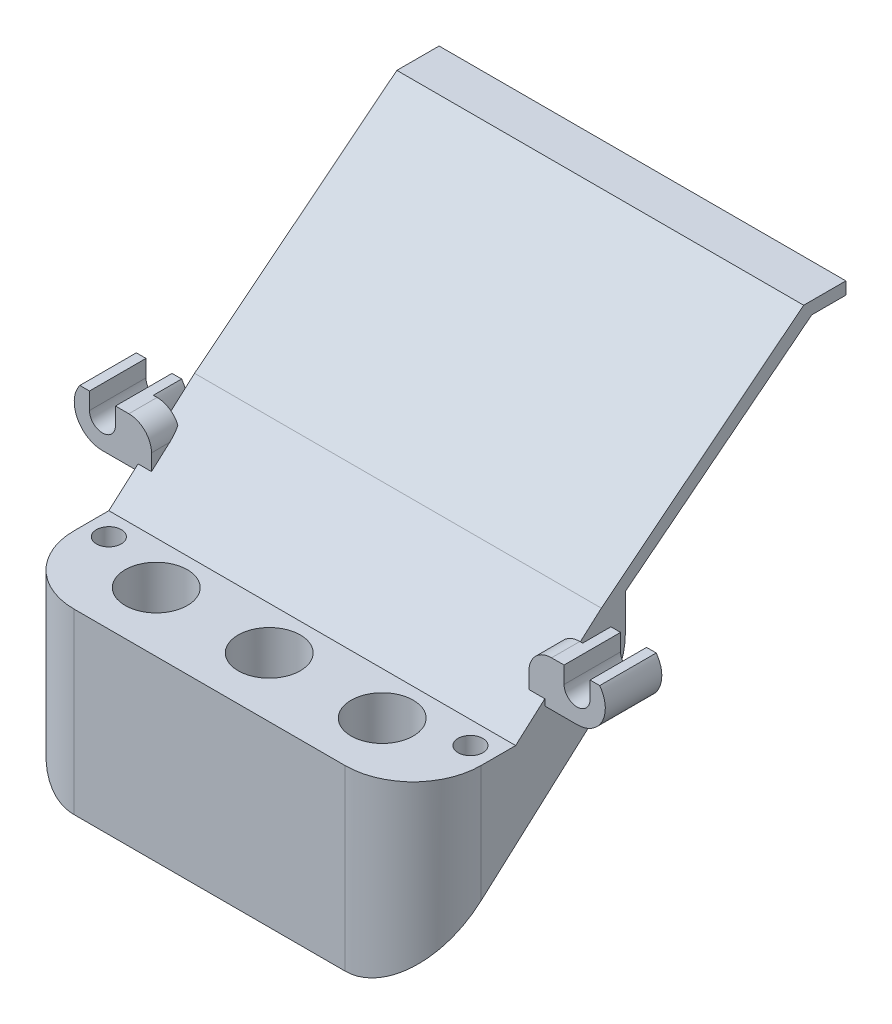
SolidWorks part; units mm, degrees
ref_plane "Plan de face" through (0, 0, 0) normal (0, 0, 1) x (1, 0, 0)
ref_plane "Plan de dessus" through (0, 0, 0) normal (0, 1, 0) x (1, 0, 0)
ref_plane "Plan de droite" through (0, 0, 0) normal (1, 0, 0) x (0, 0, -1)
sketch "Esquisse1" plane through (0, 0, 0) normal (0, 0, 1) x (1, 0, 0)
  circle A0 centre (20.8519, -74.7328) radius 1.15 construction
  circle A1 centre (20.8519, -74.7328) radius 2.5 construction
  circle A2 centre (-21.1481, -74.7328) radius 1.15 construction
  circle A3 centre (-21.1481, -74.7328) radius 2.5 construction
  circle A4 centre (20.8519, -74.7328) radius 1.15
  circle A5 centre (20.8519, -74.7328) radius 2.5
  circle A6 centre (-21.1481, -74.7328) radius 1.15
  circle A7 centre (-21.1481, -74.7328) radius 2.5
extrude "Extrusion1" add sketch "Esquisse1" along normal blind 5
ref_plane "Plan1" through (-0.172, -44.3624, -39.7148) normal (0.0029, 0.7451, 0.667) x (-1, 0.0022, 0.0019)
ref_plane "Plan3" through (0, 0, 2.5) normal (0, 0, -1) x (-1, 0, 0)
sketch "Esquisse2" plane through (0, 0, 0) normal (1, 0, 0) x (0, 0, -1)
  line L0 (-16.6644, -94.7252) -> (-16.6644, -78.9708)
  line L1 (-16.6644, -78.9708) -> (-7.5847, -78.9708)
  line L4 (0, -72.2328) -> (-7.5847, -78.9708)
  line L6 (13.7264, -67.586) -> (13.6952, -67.5462)
  line L7 (13.6952, -67.5462) -> (-23.5219, -100.8643)
  line L8 (-23.4201, -100.9942) -> (-23.4187, -100.9961)
  line L9 (-23.4187, -100.9961) -> (-14.2215, -92.7624)
  line L10 (-9.7404, -88.7476) -> (13.797, -67.6761)
  line L11 (13.797, -67.6761) -> (13.7653, -67.6356)
  line L13 (13.6952, -67.5462) -> (-16.6644, -94.7252)
  line L15 (0, -77.2328) -> (0, -72.2328) construction
  line L16 (0, -72.2328) -> (17.9041, -57.9669)
  line L17 (15.9956, -57.9652) -> (21.6434, -57.9702) construction
  line L18 (17.9041, -57.9669) -> (21.6434, -57.9702)
  line L19 (21.6434, -57.9702) -> (21.6415, -60.1702)
  line L20 (21.6415, -60.1702) -> (13.6952, -67.5462)
  spline S3 degree 3 poles (13.7653, -67.6356) (5.4607, -75.1113) (-5.0997, -84.5418) (-5.1272, -84.5067) (-5.1548, -84.4715) (5.3839, -75.0134) (13.7264, -67.586) knots 0 0 0 0 0.5 0.5 0.5 1 1 1 1 weights 1 0.596334 0.596334 1 0.596334 0.596334 1
  spline S4 degree 3 poles (-23.5219, -100.8643) (-19.5236, -97.3576) (-19.4888, -97.402) (-23.4201, -100.9942) knots 0 0 0 0 1 1 1 1 weights 1 0.974679 0.974679 1
  spline S5 degree 3 poles (-14.2215, -92.7624) (-12.7257, -91.4223) (-11.231, -90.0832) (-9.7404, -88.7476) knots 0 0 0 0 1 1 1 1
  dimension "D1" = 0
extrude "Extrusion2" add sketch "Esquisse2" along normal mid plane 36
sketch "Esquisse3" plane through (0, 0, 2.5) normal (0, 0, 1) x (1, 0, 0)
  line L0 (-23.1526, -73.2388) -> (-22.2981, -73.2388)
  line L1 (18.8474, -73.2388) -> (19.7019, -73.2388)
  line L2 (-22.2981, -74.7328) -> (-22.2981, -73.2388)
  line L3 (-19.9981, -73.2388) -> (-19.1436, -73.2388)
  line L4 (-19.9981, -74.7328) -> (-19.9981, -73.2388)
  line L5 (-21.1481, -77.2328) -> (-16.8122, -77.2328)
  line L6 (19.7019, -74.7328) -> (19.7019, -73.2388)
  line L8 (22.0019, -74.7328) -> (22.0019, -73.2388)
  line L9 (22.0019, -73.2388) -> (22.8564, -73.2388)
  line L10 (-16.8122, -77.2328) -> (-16.8122, -73.2388)
  line L11 (-16.8122, -73.2388) -> (-19.1436, -73.2388)
  line L12 (18.8474, -73.2388) -> (16.5967, -73.2388)
  line L13 (16.5967, -73.2388) -> (16.5967, -77.2328)
  line L14 (16.5967, -77.2328) -> (20.8519, -77.2328)
  circle A2 centre (-21.1481, -74.7328) radius 2.5 construction
  circle A3 centre (-21.1481, -74.7328) radius 1.15 construction
  arc A4 (-23.1526, -73.2388) -> (-21.1481, -77.2328) centre (-21.1481, -74.7328) ccw
  arc A5 (-22.2981, -74.7328) -> (-19.9981, -74.7328) centre (-21.1481, -74.7328) ccw
  circle A6 centre (20.8519, -74.7328) radius 2.5 construction
  circle A7 centre (20.8519, -74.7328) radius 1.15 construction
  arc A8 (20.8519, -77.2328) -> (22.8564, -73.2388) centre (20.8519, -74.7328) ccw
  arc A9 (19.7019, -74.7328) -> (22.0019, -74.7328) centre (20.8519, -74.7328) ccw
extrude "Extrusion3" add sketch "Esquisse3" along normal blind 2.5
sketch "Esquisse4" plane through (0, -78.9708, 0) normal (0, 1, 0) x (-1, 0, 0)
  circle A0 centre (-9.9928, 11.3854) radius 2.75
  circle A1 centre (-9.9928, 11.3854) radius 2.75
  circle A2 centre (0.0072, 11.3828) radius 2.75
  circle A3 centre (0.0072, 11.3828) radius 2.75
  circle A4 centre (10.0072, 11.3803) radius 2.75
  circle A5 centre (10.0072, 11.3803) radius 2.75
  dimension "D1" = 0
  dimension "D2" = 0
  dimension "D3" = 0
extrude "Enlèv. mat.-Extru.1" cut sketch "Esquisse4" against normal through all and the other way through all
fillet "Congé3" radius 2 2 edges at (-16.8122, -73.2388, 3.75) (16.5967, -73.2388, 3.75)
sketch "Esquisse5" plane through (0, 0, 5) normal (0, 0, 1) x (1, 0, 0)
  circle A0 centre (-21.1481, -74.7328) radius 2.5 construction
  circle A1 centre (-21.1481, -74.7328) radius 1.15 construction
  circle A2 centre (20.8519, -74.7328) radius 1.15 construction
  circle A3 centre (20.8519, -74.7328) radius 2.5 construction
  circle A4 centre (-21.1481, -74.7328) radius 2.5
  circle A5 centre (-21.1481, -74.7328) radius 1.15
  circle A6 centre (20.8519, -74.7328) radius 1.15
  circle A7 centre (20.8519, -74.7328) radius 2.5
extrude "Enlèv. mat.-Extru.2" [suppressed] cut sketch "Esquisse5" against normal blind 2.5
sketch "Esquisse6" plane through (0, 0, 5) normal (0, 0, 1) x (1, 0, 0)
  line L7 (19.7019, -73.2388) -> (18.8474, -73.2388)
  line L8 (18.8474, -73.2388) -> (16.5967, -73.2388)
  line L9 (16.5967, -73.2388) -> (16.5967, -77.2328)
  line L10 (16.5967, -77.2328) -> (20.8519, -77.2328)
  line L11 (22.8564, -73.2388) -> (22.0019, -73.2388)
  line L12 (22.0019, -73.2388) -> (22.0019, -74.7328)
  line L13 (19.7019, -74.7328) -> (19.7019, -73.2388)
  line L14 (19.7019, -73.2388) -> (18.8474, -73.2388)
  line L18 (22.8564, -73.2388) -> (22.0019, -73.2388)
  line L19 (22.0019, -73.2388) -> (22.0019, -74.7328)
  line L20 (19.7019, -74.7328) -> (19.7019, -73.2388)
  line L21 (-21.1481, -77.2328) -> (-16.8122, -77.2328)
  line L22 (-16.8122, -77.2328) -> (-16.8122, -73.2388)
  line L23 (-16.8122, -73.2388) -> (-19.1436, -73.2388)
  line L24 (-19.1436, -73.2388) -> (-19.9981, -73.2388)
  line L25 (-19.9981, -73.2388) -> (-19.9981, -74.7328)
  line L26 (-22.2981, -74.7328) -> (-22.2981, -73.2388)
  line L27 (-22.2981, -73.2388) -> (-23.1526, -73.2388)
  line L31 (-19.1436, -73.2388) -> (-19.9981, -73.2388)
  line L32 (-19.9981, -73.2388) -> (-19.9981, -74.7328)
  line L33 (-22.2981, -74.7328) -> (-22.2981, -73.2388)
  line L34 (-22.2981, -73.2388) -> (-23.1526, -73.2388)
  arc A0 (20.8519, -77.2328) -> (18.8474, -73.2388) centre (20.8519, -74.7328) ccw construction
  arc A1 (22.8564, -73.2388) -> (18.8474, -73.2388) centre (20.8519, -74.7328) ccw
  arc A2 (20.8519, -77.2328) -> (22.8564, -73.2388) centre (20.8519, -74.7328) ccw
  arc A3 (19.7019, -74.7328) -> (22.0019, -74.7328) centre (20.8519, -74.7328) ccw
  arc A4 (-19.1436, -73.2388) -> (-21.1481, -77.2328) centre (-21.1481, -74.7328) ccw construction
  arc A5 (19.7019, -74.7328) -> (22.0019, -74.7328) centre (20.8519, -74.7328) ccw
  arc A6 (-23.1526, -73.2388) -> (-21.1481, -77.2328) centre (-21.1481, -74.7328) ccw
  arc A7 (-22.2981, -74.7328) -> (-19.9981, -74.7328) centre (-21.1481, -74.7328) ccw
  arc A9 (-22.2981, -74.7328) -> (-19.9981, -74.7328) centre (-21.1481, -74.7328) ccw
  arc A10 (-19.1436, -73.2388) -> (-23.1526, -73.2388) centre (-21.1481, -74.7328) ccw
  dimension "D1" = 0
  dimension "D2" = 0
extrude "Enlèv. mat.-Extru.3" cut sketch "Esquisse6" against normal through all
sketch "Esquisse7" plane through (18, 0, 0) normal (1, 0, 0) x (0, 0, -1)
  line L0 (22.3876, -59.0664) -> (18.6199, -59.0664)
  line L2 (18.6199, -59.0664) -> (2.1273, -72.0094)
  line L3 (2.1273, -72.0094) -> (2.1273, -79.6896)
  line L4 (2.1273, -79.6896) -> (22.3876, -60.2155)
  line L5 (22.3876, -60.2155) -> (22.3876, -59.0664)
extrude "Enlèv. mat.-Extru.5" cut sketch "Esquisse7" against normal through all
sketch "Esquisse8" plane through (0, -44.3015, -39.6602) normal (0, -0.7451, -0.667) x (1, 0, 0)
  line L1 (16.2244, 59.7434) -> (-16.434, 59.7434)
  line L2 (16.2244, 59.7434) -> (16.2244, 40.56)
  line L3 (16.2244, 40.56) -> (-16.434, 40.56)
  line L4 (-16.434, 59.7434) -> (-16.434, 40.56)
extrude "Enlèv. mat.-Extru.6" cut sketch "Esquisse8" against normal up to surface (5.2533 mm away)
fillet "Congé4" radius 6 2 edges at (-17.217, -77.9023, -2.1273) (17.1122, -77.9023, -2.1273)
fillet "Congé5" radius 6 2 edges at (-18, -86.848, 16.6644) (18, -86.848, 16.6644)
sketch "Esquisse9" plane through (0, -78.9708, 0) normal (0, 1, 0) x (-1, 0, 0)
  line L0 (-18, 7.5847) -> (18, 7.5847) construction
  line L1 (-18, 7.5847) -> (-18, 10.6644) construction
  line L2 (18, 7.5847) -> (18, 10.6644) construction
  circle A0 centre (-16, 9.5847) radius 1.1
  circle A1 centre (16, 9.5847) radius 1.1
  dimension "D1" = 2.2
  dimension "D2" = 2
  dimension "D3" = 2
  dimension "D4" = 2
extrude "Enlèv. mat.-Extru.7" cut sketch "Esquisse9" against normal blind 6
